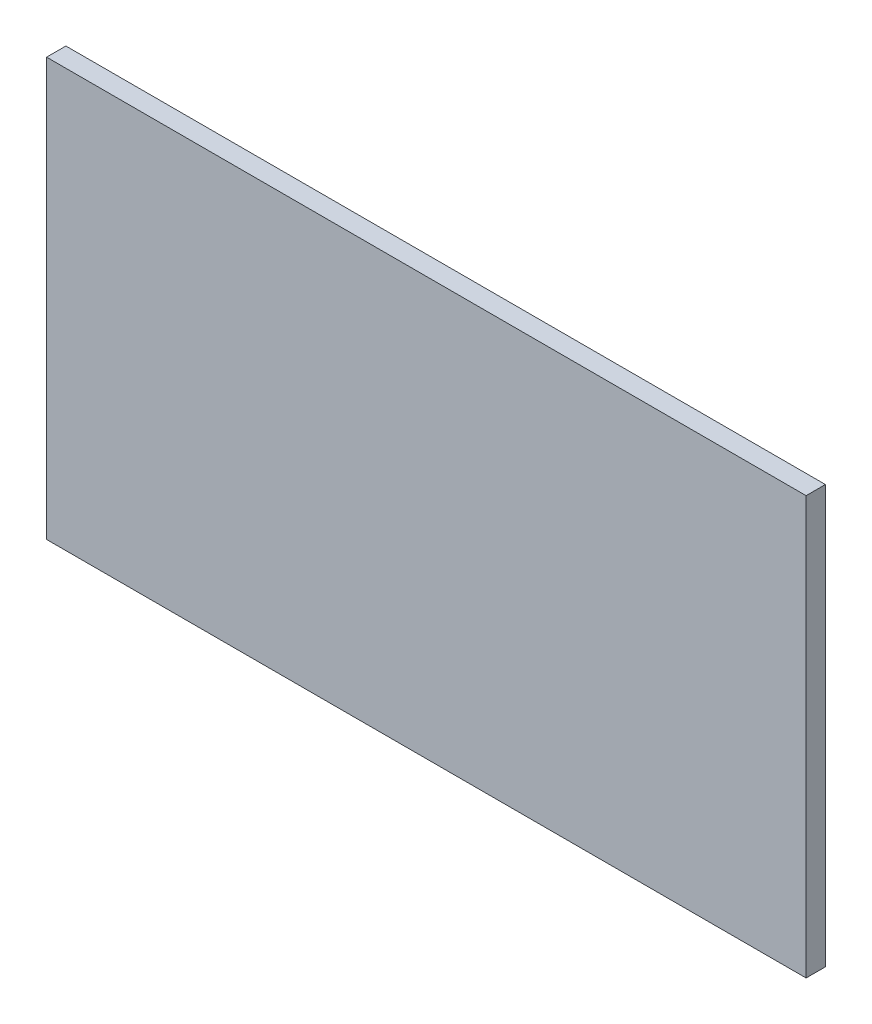
SolidWorks part; units mm, degrees
ref_plane "Front Plane" through (0, 0, 0) normal (0, 0, 1) x (1, 0, 0)
ref_plane "Top Plane" through (0, 0, 0) normal (0, 1, 0) x (1, 0, 0)
ref_plane "Right Plane" through (0, 0, 0) normal (1, 0, 0) x (0, 0, -1)
sketch "Sketch1" plane through (0, 0, 0) normal (0, 0, 1) x (1, 0, 0)
  line L1 (-50, 27.5) -> (50, 27.5)
  line L2 (-50, 27.5) -> (-50, -27.5)
  line L3 (-50, -27.5) -> (50, -27.5)
  line L4 (50, 27.5) -> (50, -27.5)
  line L5 (-50, 27.5) -> (50, -27.5) construction
  line L6 (-50, -27.5) -> (50, 27.5) construction
  point P0 (0, 0)
  dimension "D1" = 55
  dimension "D2" = 100
extrude "Boss-Extrude1" add sketch "Sketch1" along normal blind 2.54
